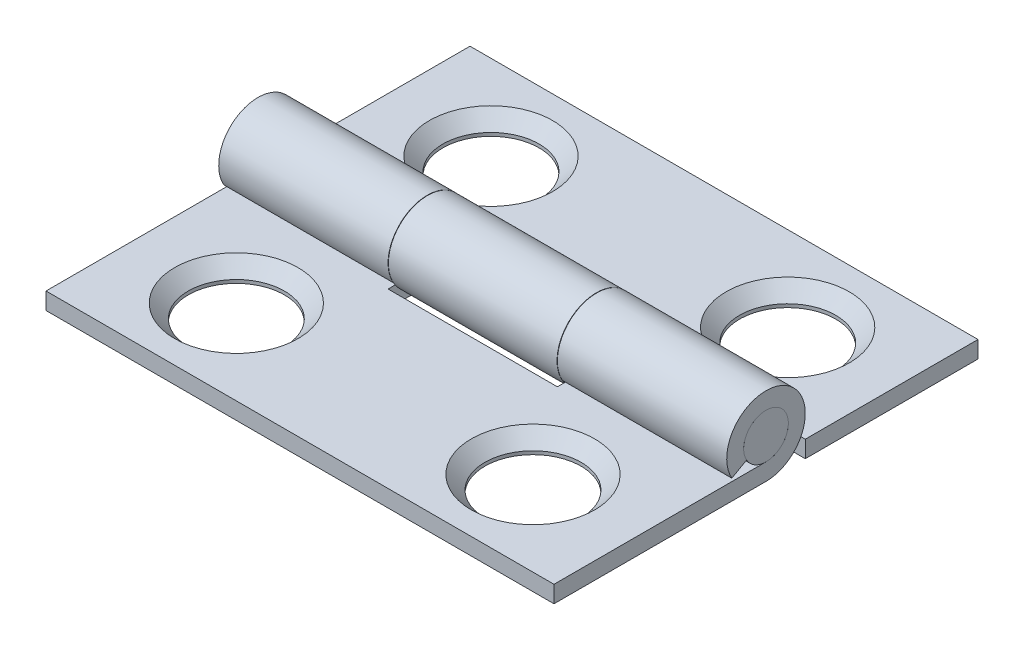
SolidWorks part; units mm, degrees
material "Brass"
ref_plane "Front Plane" through (0, 0, 0) normal (0, 0, 1) x (1, 0, 0)
ref_plane "Top Plane" through (0, 0, 0) normal (0, 1, 0) x (1, 0, 0)
ref_plane "Right Plane" through (0, 0, 0) normal (1, 0, 0) x (0, 0, -1)
sketch "Sketch1" plane through (0, 0, 0) normal (0, 1, 0) x (1, 0, 0)
  line L0 (-9.525, 0) -> (9.525, 0) construction
  line L1 (-9.525, -7.9502) -> (-9.525, 7.9502) construction
  line L2 (-9.525, -7.9502) -> (-5.5626, -7.9502) construction
  line L3 (5.5626, -4.7752) -> (-5.5626, -4.7752) construction
  line L4 (-5.5626, -7.9502) -> (5.5626, -7.9502) construction
  line L5 (9.525, -7.9502) -> (9.525, -4.7752) construction
  line L6 (5.5626, -7.9502) -> (9.525, -7.9502) construction
  line L7 (-9.525, 7.9502) -> (-4.7498, 7.9502) construction
  line L8 (-4.7498, 7.9502) -> (11.1252, 7.9502) construction
  line L9 (11.1252, 7.9502) -> (27.0002, 7.9502) construction
  line L10 (27.0002, 7.9502) -> (30.9626, 7.9502) construction
  line L11 (5.5626, -7.0866) -> (5.5626, -2.4638) construction
  line L12 (5.5626, -4.7752) -> (9.525, -4.7752) construction
  line L13 (-5.5626, -4.7752) -> (-5.5626, -7.9502) construction
  line L14 (5.5626, 4.7752) -> (-5.5626, 4.7752) construction
  point P3 (5.5626, -6.5786)
  point P4 (0, 0)
  point P8 (-9.525, 0)
  point P17 (-3.175, 0)
  point P21 (5.5626, -4.7752)
  dimension "Frame Leaf Height" = 19.05
  dimension "Overall Width" = 15.9004
  dimension "Hole to End 1" = 3.9624
  dimension "Hole to End 2" = 3.9624
  dimension "D1" = 3.9624
  dimension "D2" = 4.7752
  dimension "D4" = 15.875
  dimension "D6" = 15.875
  dimension "Knuckle Length" = 6.35
  dimension "Hole Chamfer Dia" = 4.6228
  dimension "Hole Center to Pin" = 4.7752
  dimension "Door Leaf Height" = 19.05
  dimension "Mounting Hole Diameter" = 3.6068
  dimension "D3" = 11.1252
  dimension "Frame Leaf Width" = 7.9502
  dimension "Door Leaf Width" = 7.9502
sketch "Sketch2" plane through (0, 0, 0) normal (1, 0, 0) x (0, 0, -1)
  line L2 (0, -1.4732) -> (0, -0.8382) construction
  line L4 (0, 0.8382) -> (0, -0.8382) construction
  point P8 (0, 0)
  dimension "Leaf Thickness" = 0.635
  dimension "Pin Diameter" = 1.6764
sketch "Sketch3" plane through (0, 0, 0) normal (1, 0, 0) x (0, 0, -1)
  line L3 (0, 0) -> (-1.4732, -0.8382) construction
  line L4 (0, -1.4732) -> (-7.9502, -1.4732)
  line L5 (-7.9502, -1.4732) -> (-7.9502, -0.8382)
  line L7 (-7.9502, -0.8382) -> (0, -0.8382)
  line L8 (-7.9502, 0) -> (7.9502, 0) construction
  line L9 (-0.7285, -0.4145) -> (-1.2805, -0.7285)
  line L11 (-1.4732, 0) -> (-1.4732, -0.8382) construction
  circle A4 centre (0, 0) radius 0.8382 construction
  circle A5 centre (0, 0) radius 1.4732 construction
  arc A8 (-0.7285, -0.4145) -> (0, -0.8382) centre (0, 0) cw
  arc A9 (-1.2805, -0.7285) -> (0, -1.4732) centre (0, 0) cw
  point P0 (-1.2805, -0.7285)
  point P13 (-0.7285, -0.4145)
extrude "Boss-Extrude1" add sketch "Sketch3" along normal mid plane 19.05
pattern_circular "CirPattern1" count 2 over 360 about axis through (0, 0, 0) along (0, 1, 0) of bodies 104 107
sketch "Sketch4" plane through (0, 0, 0) normal (0, 1, 0) x (1, 0, 0)
  line L0 (-9.525, -1.4732) -> (9.525, -1.4732) construction
  line L1 (-9.525, -1.4732) -> (9.525, -1.4732) construction
  line L2 (9.525, 1.4732) -> (-9.525, 1.4732) construction
  line L3 (9.525, 1.4732) -> (-9.525, 1.4732) construction
  line L4 (-3.175, -1.4732) -> (-3.175, 1.4732)
  line L6 (-3.175, 1.4732) -> (3.175, 1.4732)
  line L7 (3.175, -1.4732) -> (-3.175, -1.4732)
  line L8 (3.175, 1.4732) -> (3.175, -1.4732)
  point P8 (-3.175, 0)
  dimension "D1" = 6.35
extrude "Cut-Extrude1" cut sketch "Sketch4" against normal through all both and the other way through all
sketch "Sketch10" plane through (0, 0, 0) normal (0, 1, 0) x (1, 0, 0)
  line L0 (9.525, 1.4732) -> (-9.525, 1.4732) construction
  line L5 (-3.1623, 1.4732) -> (-9.525, 1.4732)
  line L6 (-3.1623, 1.4732) -> (-3.1623, -1.4732)
  line L7 (-3.1623, -1.4732) -> (-9.525, -1.4732)
  line L8 (-9.525, 1.4732) -> (-9.525, -1.4732)
  line L9 (3.1623, 1.4732) -> (9.525, 1.4732)
  line L10 (3.1623, 1.4732) -> (3.1623, -1.4732)
  line L11 (3.1623, -1.4732) -> (9.525, -1.4732)
  line L12 (9.525, 1.4732) -> (9.525, -1.4732)
  dimension "D1" = 0.0127
extrude "Cut-Extrude4" cut sketch "Sketch10" against normal through all both and the other way through all
sketch "Sketch5" plane through (0, -0.8382, 0) normal (0, 1, 0) x (1, 0, 0)
  line L0 (5.5626, -4.7752) -> (-5.5626, -4.7752) construction
  line L1 (0, -4.7752) -> (0, -7.9502) construction
  line L2 (-5.5626, -4.7752) -> (-5.5626, -7.9502) construction
  line L3 (9.525, -7.9502) -> (-9.525, -7.9502) construction
  circle A0 centre (5.5626, -4.7752) radius 2.3114
  circle A2 centre (-5.5626, -4.7752) radius 2.3114
extrude "Cut-Extrude2" cut sketch "Sketch5" against normal through all draft 45
sketch "Sketch9" plane through (0, 0, 0) normal (0, 1, 0) x (1, 0, 0)
  circle A0 centre (5.5626, -4.7752) radius 1.8034
  circle A2 centre (-5.5626, -4.7752) radius 1.8034
  dimension "D1" = 3.6068
extrude "Cut-Extrude3" cut sketch "Sketch9" against normal through all both and the other way through all
sketch "Sketch11" plane through (0, -0.8382, 0) normal (0, 1, 0) x (1, 0, 0)
  circle A0 centre (5.5626, 4.7752) radius 2.3114
  circle A1 centre (-5.5626, 4.7752) radius 2.3114
  circle A2 centre (-5.5626, -4.7752) radius 2.3114 construction
extrude "Cut-Extrude5" cut sketch "Sketch11" against normal through all draft 45
sketch "Sketch12" plane through (0, -0.8382, 0) normal (0, 1, 0) x (1, 0, 0)
  circle A0 centre (-5.5626, 4.7752) radius 1.8034
  circle A1 centre (5.5626, 4.7752) radius 1.8034
  circle A2 centre (-5.5626, -4.7752) radius 1.8034 construction
extrude "Cut-Extrude6" cut sketch "Sketch12" against normal through all both and the other way through all
sketch "Sketch6" plane through (0, 0, 0) normal (1, 0, 0) x (0, 0, -1)
  circle A0 centre (0, 0) radius 0.8382
  dimension "D1" = 1.6764
extrude "Boss-Extrude2" add sketch "Sketch6" along normal mid plane 19.05 separate body
sketch "Sketch7" plane through (0, 0, 0) normal (1, 0, 0) x (0, 0, -1)
  line L0 (-0.8382, 0) -> (0.8382, 0) construction
  line L1 (-7.9502, 0) -> (7.9502, 0) construction
  line L2 (7.9502, -0.8382) -> (7.9502, -1.4732) construction
  line L3 (7.9502, -0.8382) -> (7.9502, -1.4732) construction
  line L4 (7.9502, -1.4732) -> (-7.9502, -1.4732) construction
  line L5 (-7.9502, -1.4732) -> (-7.9502, -0.8382)
  point P6 (0, 0)
  point P8 (0.8382, 0)
  point P9 (-0.8382, 0)
  point P12 (7.9502, -0.8382)
  point P13 (7.9502, -1.4732)
  point P14 (-7.9502, -1.4732)
  dimension "D1" = 1.6764
  dimension "D2" = 15.9004
  dimension "D3" = 0.635
sketch "Sketch8" plane through (0, 0, 0) normal (0, 1, 0) x (1, 0, 0)
  line L0 (-7.874, -4.7752) -> (-3.2512, -4.7752) construction
  line L1 (5.5626, 4.7752) -> (-5.5626, 4.7752) construction
  line L2 (3.2512, -4.7752) -> (7.874, -4.7752) construction
  line L3 (-5.5626, -2.4638) -> (-5.5626, -7.0866) construction
  line L5 (5.5626, -2.4638) -> (5.5626, -7.0866) construction
  line L6 (-5.5626, 7.0866) -> (-5.5626, 2.4638) construction
  line L7 (-7.874, 4.7752) -> (-3.2512, 4.7752) construction
  line L10 (5.5626, 7.0866) -> (5.5626, 2.4638) construction
  line L11 (3.2512, 4.7752) -> (7.874, 4.7752) construction
  line L12 (5.5626, 4.7752) -> (7.197, 6.4096) construction
  circle A1 centre (-5.5626, -4.7752) radius 2.3114 construction
  circle A3 centre (5.5626, -4.7752) radius 2.3114 construction
  circle A7 centre (5.5626, 4.7752) radius 2.3114 construction
  circle A8 centre (-5.5626, 4.7752) radius 2.3114 construction
  circle A9 centre (5.5626, 4.7752) radius 2.3114 construction
  point P2 (-9.525, 0)
  point P7 (-5.5626, -4.7752)
  point P19 (5.5626, -4.7752)
  point P25 (-9.525, 7.9502)
  point P26 (30.9626, 7.9502)
  point P28 (-9.525, -7.9502)
  point P30 (9.525, -7.9502)
  point P32 (-7.874, -4.7752)
  point P33 (-5.5626, -2.4638)
  point P34 (-3.2512, -4.7752)
  point P35 (-5.5626, -7.0866)
  point P40 (7.874, -4.7752)
  point P41 (5.5626, -7.0866)
  point P42 (3.2512, -4.7752)
  point P43 (5.5626, -2.4638)
  point P67 (5.5626, -7.9502)
  point P69 (-5.5626, -7.9502)
  point P71 (-4.7498, 7.9502)
  point P73 (-5.5626, 4.7752)
  point P76 (5.5626, 4.7752)
  point P77 (27.0002, 7.9502)
  point P78 (11.1252, 7.9502)
  point P82 (-5.5626, 7.0866)
  point P83 (-7.874, 4.7752)
  point P84 (-5.5626, 2.4638)
  point P85 (-3.2512, 4.7752)
  point P90 (5.5626, 2.4638)
  point P91 (3.2512, 4.7752)
  point P92 (5.5626, 7.0866)
  point P97 (7.197, 6.4096)
  dimension "D1" = 45
equation "\"D1@Sketch1\"=\"Hole to End 1@Sketch1\""
equation "\"D6@Sketch1\"=\"D4@Sketch1\""
equation "\"D1@Boss-Extrude1\" = \"Frame Leaf Height@Sketch1\""
equation "\"D1@Sketch4\"=\"Knuckle Length@Sketch1\""
equation "\"D1@Sketch6\"=\"Pin Diameter@Sketch2\""
equation "\"D1@Boss-Extrude2\" = \"Frame Leaf Height@Sketch1\""
equation "\"D1@Sketch7\"=\"Pin Diameter@Sketch2\""
equation "\"D2@Sketch7\"=\"Overall Width@Sketch1\""
equation "\"D3@Sketch7\"=\"Leaf Thickness@Sketch2\""
equation "\"Knuckle Length@Sketch1\"=\"Frame Leaf Height@Sketch1\" / 3"
equation "\"Hole to End 2@Sketch1\"=\"Hole to End 1@Sketch1\""
equation "\"D1@Sketch9\"=\"Mounting Hole Diameter@Sketch1\""
equation "\"Hole Chamfer Dia@Sketch1\"=\"Mounting Hole Diameter@Sketch1\"+.04"
